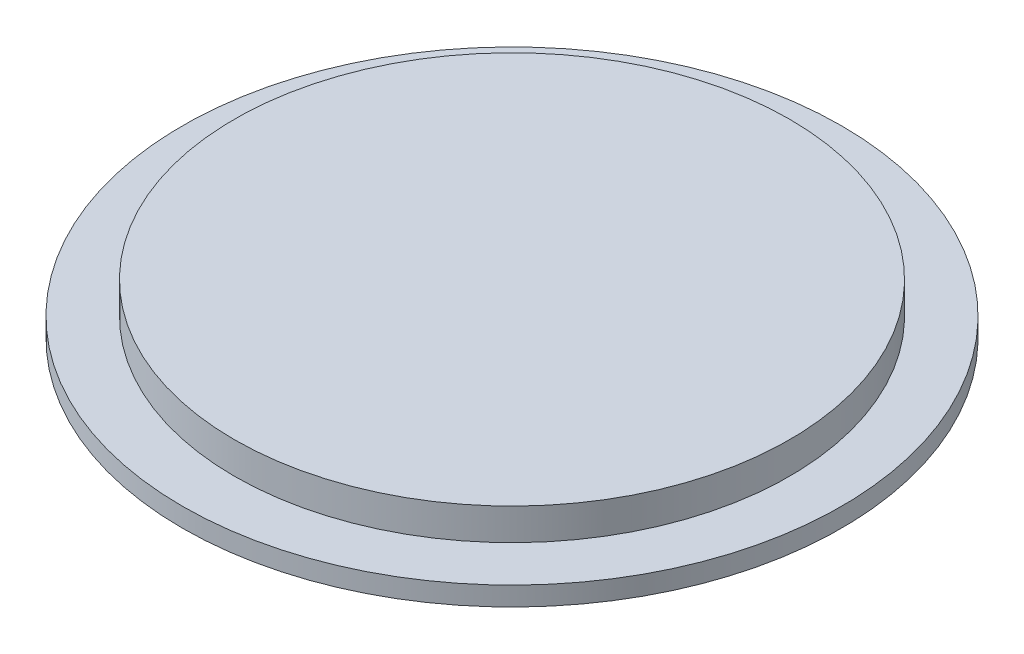
SolidWorks part; units mm, degrees
ref_plane "Front Plane" through (0, 0, 0) normal (0, 0, 1) x (1, 0, 0)
ref_plane "Top Plane" through (0, 0, 0) normal (0, 1, 0) x (1, 0, 0)
ref_plane "Right Plane" through (0, 0, 0) normal (1, 0, 0) x (0, 0, -1)
sketch "Sketch1" plane through (0, 0, 0) normal (0, 1, 0) x (1, 0, 0)
  circle A0 centre (0, 0) radius 52
  dimension "D1" = 104
extrude "Boss-Extrude1" add sketch "Sketch1" along normal blind 3
sketch "Sketch2" plane through (0, 3, 0) normal (0, 1, 0) x (1, 0, 0)
  circle A0 centre (0, 0) radius 43.8
  dimension "D1" = 87.6
extrude "Boss-Extrude2" add sketch "Sketch2" along normal blind 5
